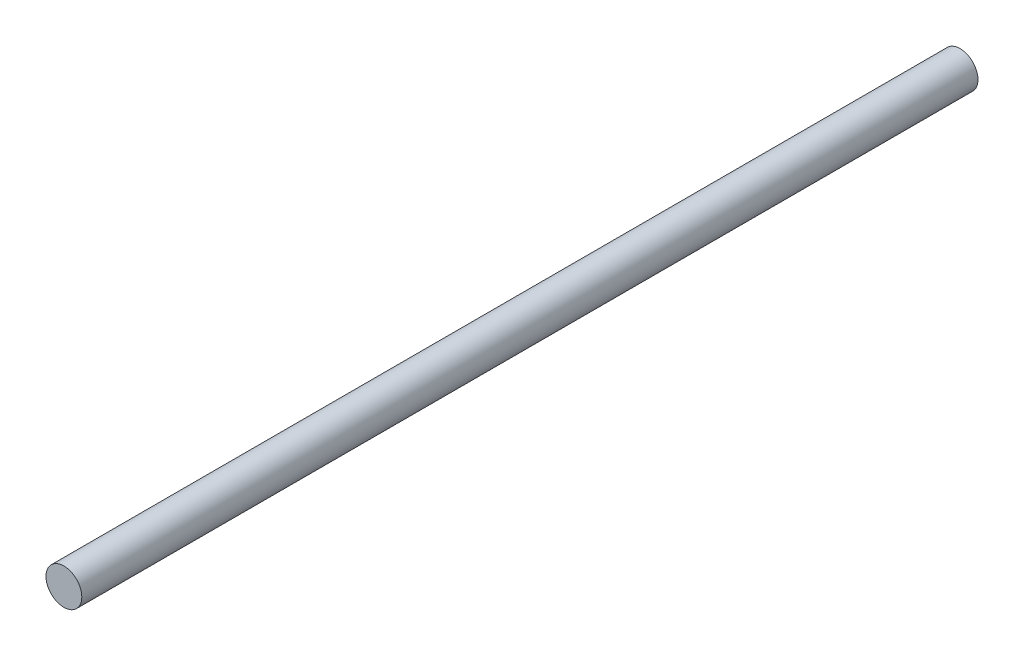
SolidWorks part; units mm, degrees
ref_plane "前视基准面" through (0, 0, 0) normal (0, 0, 1) x (1, 0, 0)
ref_plane "上视基准面" through (0, 0, 0) normal (0, 1, 0) x (1, 0, 0)
ref_plane "右视基准面" through (0, 0, 0) normal (1, 0, 0) x (0, 0, -1)
sketch "草图1" plane through (0, 0, 0) normal (0, 0, 1) x (1, 0, 0)
  circle A0 centre (0, 0) radius 8
  dimension "D1" = 16
extrude "凸台-拉伸1" add sketch "草图1" along normal blind 400
